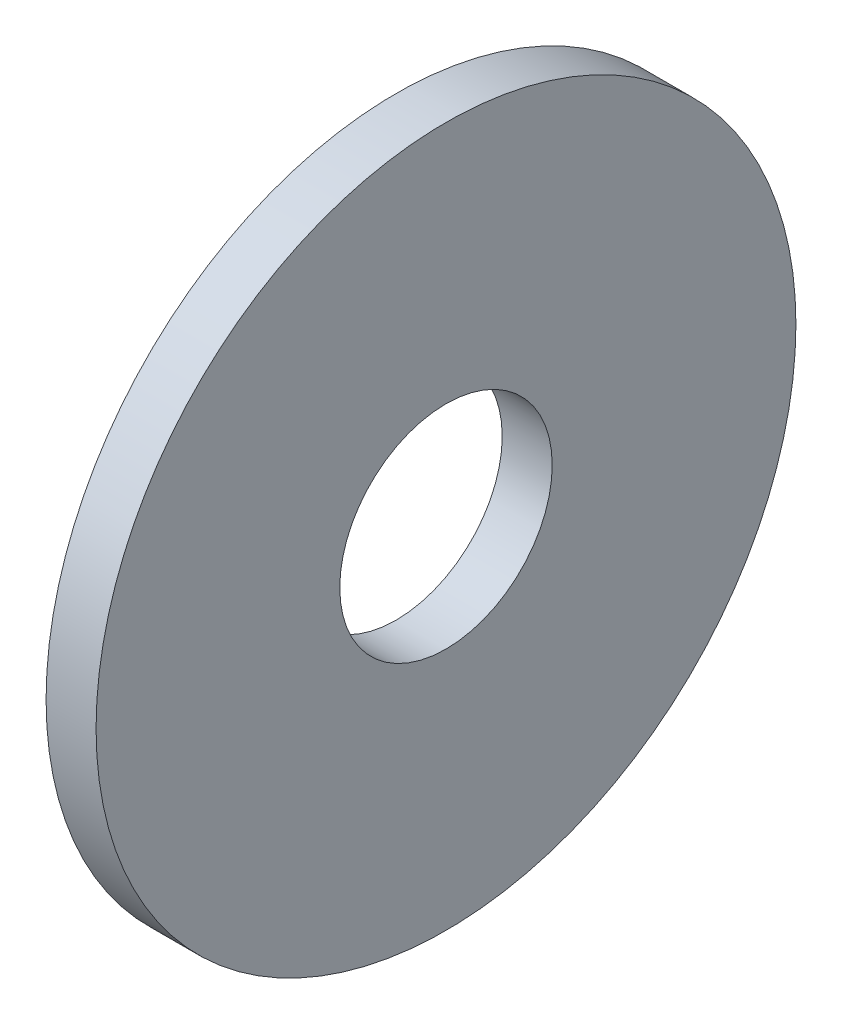
SolidWorks part; units mm, degrees
material "SS400"
ref_plane "Front Plane" through (0, 0, 0) normal (0, 0, 1) x (1, 0, 0)
ref_plane "Top Plane" through (0, 0, 0) normal (0, 1, 0) x (1, 0, 0)
ref_plane "Right Plane" through (0, 0, 0) normal (1, 0, 0) x (0, 0, -1)
sketch "Sketch1" plane through (0, 0, 0) normal (1, 0, 0) x (0, 0, -1)
  circle A0 centre (0, 0) radius 4.25
  circle A1 centre (0, 0) radius 14
  dimension "D1" = 8.5
  dimension "D2" = 28
extrude "Boss-Extrude1" add sketch "Sketch1" along normal mid plane 2
equation "\"Mass Kg\"= \"SW-Mass\""
